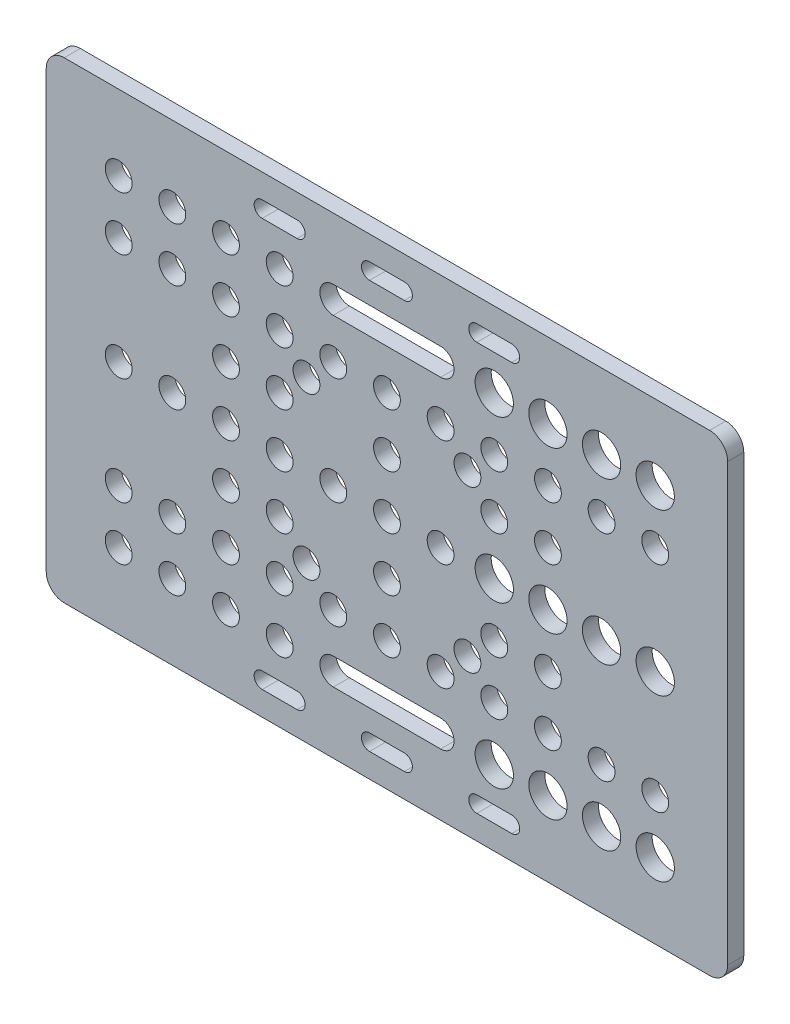
SolidWorks part; units mm, degrees
ref_plane "Plan de face" through (0, 0, 0) normal (0, 0, 1) x (1, 0, 0)
ref_plane "Plan de dessus" through (0, 0, 0) normal (0, 1, 0) x (1, 0, 0)
ref_plane "Plan de droite" through (0, 0, 0) normal (1, 0, 0) x (0, 0, -1)
sketch "Esquisse1" plane through (0, 0, 0) normal (0, 0, 1) x (1, 0, 0)
  line L0 (0, -44) -> (0, 44) construction
  line L1 (-60.14, -44) -> (60.14, -44)
  line L2 (-63.5, -40.64) -> (-63.5, 40.64)
  line L3 (-60.14, 44) -> (60.14, 44)
  line L4 (63.5, -40.64) -> (63.5, 40.64)
  line L5 (-63.5, -44) -> (63.5, 44) construction
  line L6 (-63.5, 44) -> (63.5, -44) construction
  line L7 (-10, -30) -> (10, -30) construction
  line L8 (-63.5, 0) -> (63.5, 0) construction
  line L9 (-10, -27.5) -> (10, -27.5)
  line L10 (-10, -32.5) -> (10, -32.5)
  line L11 (-23.25, -38.02) -> (-16.75, -38.02) construction
  line L12 (-23.25, -36.52) -> (-16.75, -36.52)
  line L13 (-23.25, -39.52) -> (-16.75, -39.52)
  line L14 (-20, -38.02) -> (-20, -30) construction
  line L15 (-3.25, -38.02) -> (3.25, -38.02) construction
  line L16 (-3.25, -36.52) -> (3.25, -36.52)
  line L17 (-3.25, -39.52) -> (3.25, -39.52)
  line L18 (16.75, -38.02) -> (23.25, -38.02) construction
  line L19 (16.75, -36.52) -> (23.25, -36.52)
  line L20 (16.75, -39.52) -> (23.25, -39.52)
  line L21 (-30, 0) -> (-30, -20) construction
  line L22 (-20, -10) -> (-10, -20) construction
  line L23 (-10, 30) -> (10, 30) construction
  line L24 (10, -20) -> (20, -10) construction
  line L25 (-10, 27.5) -> (10, 27.5)
  line L26 (-10, 32.5) -> (10, 32.5)
  line L27 (-23.25, 38.02) -> (-16.75, 38.02) construction
  line L28 (-23.25, 36.52) -> (-16.75, 36.52)
  line L29 (-23.25, 39.52) -> (-16.75, 39.52)
  line L30 (-3.25, 38.02) -> (3.25, 38.02) construction
  line L31 (-3.25, 36.52) -> (3.25, 36.52)
  line L32 (-3.25, 39.52) -> (3.25, 39.52)
  line L33 (16.75, 38.02) -> (23.25, 38.02) construction
  line L34 (16.75, 36.52) -> (23.25, 36.52)
  line L35 (16.75, 39.52) -> (23.25, 39.52)
  line L36 (10, 20) -> (20, 10) construction
  line L37 (-20, 10) -> (-10, 20) construction
  line L38 (-20, 38.02) -> (-20, 30) construction
  line L39 (-10, 30) -> (10, -30) construction
  line L40 (-10, -30) -> (10, 30) construction
  arc A0 (-60.14, -44) -> (-63.5, -40.64) centre (-60.14, -40.64) cw
  arc A1 (60.14, -44) -> (63.5, -40.64) centre (60.14, -40.64) ccw
  arc A2 (60.14, 44) -> (63.5, 40.64) centre (60.14, 40.64) cw
  arc A3 (-63.5, 40.64) -> (-60.14, 44) centre (-60.14, 40.64) cw
  circle A4 centre (0, -20) radius 2.5
  circle A5 centre (10, -20) radius 2.5
  circle A6 centre (20, -20) radius 2.5
  circle A7 centre (30, -20) radius 2.5
  circle A8 centre (40, -20) radius 2.5
  circle A9 centre (50, -20) radius 2.5
  circle A10 centre (-10, -20) radius 2.5
  circle A11 centre (-20, -20) radius 2.5
  circle A12 centre (-30, -20) radius 2.5
  circle A13 centre (-40, -20) radius 2.5
  circle A14 centre (-50, -20) radius 2.5
  circle A15 centre (-50, -30) radius 2.5
  circle A16 centre (-40, -30) radius 2.5
  circle A17 centre (-30, -30) radius 2.5
  circle A18 centre (-20, -30) radius 2.5
  circle A19 centre (50, -30) radius 3.57
  circle A20 centre (40, -30) radius 3.57
  circle A21 centre (30, -30) radius 3.57
  circle A22 centre (20, -30) radius 3.57
  arc A23 (-10, -27.5) -> (-10, -32.5) centre (-10, -30) ccw
  arc A24 (10, -32.5) -> (10, -27.5) centre (10, -30) ccw
  arc A25 (-23.25, -36.52) -> (-23.25, -39.52) centre (-23.25, -38.02) ccw
  arc A26 (-16.75, -39.52) -> (-16.75, -36.52) centre (-16.75, -38.02) ccw
  arc A27 (-3.25, -36.52) -> (-3.25, -39.52) centre (-3.25, -38.02) ccw
  arc A28 (3.25, -39.52) -> (3.25, -36.52) centre (3.25, -38.02) ccw
  arc A29 (16.75, -36.52) -> (16.75, -39.52) centre (16.75, -38.02) ccw
  arc A30 (23.25, -39.52) -> (23.25, -36.52) centre (23.25, -38.02) ccw
  circle A31 centre (-50, 0) radius 2.5
  circle A32 centre (-40, 0) radius 2.5
  circle A33 centre (-30, 0) radius 2.5
  circle A34 centre (-20, 0) radius 2.5
  circle A35 centre (-10, 0) radius 2.5
  circle A36 centre (0, 0) radius 2.5
  circle A37 centre (10, 0) radius 2.5
  circle A38 centre (20, 0) radius 3.57
  circle A39 centre (30, 0) radius 3.57
  circle A40 centre (40, 0) radius 3.57
  circle A41 centre (50, 0) radius 3.57
  circle A42 centre (-30, -10) radius 2.5
  circle A43 centre (-20, -10) radius 2.5
  circle A44 centre (20, -10) radius 2.5
  circle A45 centre (30, -10) radius 2.5
  circle A46 centre (0, -10) radius 2.5
  circle A47 centre (-15, -15) radius 2.5
  circle A48 centre (15, -15) radius 2.5
  circle A49 centre (50, 0) radius 2.5 [skipped]
  circle A50 centre (40, 0) radius 2.5 [skipped]
  circle A51 centre (30, 0) radius 2.5 [skipped]
  circle A52 centre (20, 0) radius 2.5 [skipped]
  arc A53 (-10, 27.5) -> (-10, 32.5) centre (-10, 30) cw
  arc A54 (10, 32.5) -> (10, 27.5) centre (10, 30) cw
  arc A55 (-23.25, 36.52) -> (-23.25, 39.52) centre (-23.25, 38.02) cw
  arc A56 (-16.75, 39.52) -> (-16.75, 36.52) centre (-16.75, 38.02) cw
  arc A57 (-3.25, 36.52) -> (-3.25, 39.52) centre (-3.25, 38.02) cw
  arc A58 (3.25, 39.52) -> (3.25, 36.52) centre (3.25, 38.02) cw
  arc A59 (16.75, 36.52) -> (16.75, 39.52) centre (16.75, 38.02) cw
  arc A60 (23.25, 39.52) -> (23.25, 36.52) centre (23.25, 38.02) cw
  circle A61 centre (15, 15) radius 2.5
  circle A62 centre (-15, 15) radius 2.5
  circle A63 centre (0, 10) radius 2.5
  circle A64 centre (30, 10) radius 2.5
  circle A65 centre (20, 10) radius 2.5
  circle A66 centre (-20, 10) radius 2.5
  circle A67 centre (-30, 10) radius 2.5
  circle A68 centre (20, 30) radius 3.57
  circle A69 centre (30, 30) radius 3.57
  circle A70 centre (40, 30) radius 3.57
  circle A71 centre (50, 30) radius 3.57
  circle A72 centre (-20, 30) radius 2.5
  circle A73 centre (-30, 30) radius 2.5
  circle A74 centre (-40, 30) radius 2.5
  circle A75 centre (-50, 30) radius 2.5
  circle A76 centre (-50, 20) radius 2.5
  circle A77 centre (-40, 20) radius 2.5
  circle A78 centre (-30, 20) radius 2.5
  circle A79 centre (-20, 20) radius 2.5
  circle A80 centre (-10, 20) radius 2.5
  circle A81 centre (50, 20) radius 2.5
  circle A82 centre (40, 20) radius 2.5
  circle A83 centre (30, 20) radius 2.5
  circle A84 centre (20, 20) radius 2.5
  circle A85 centre (10, 20) radius 2.5
  circle A86 centre (0, 20) radius 2.5
  point P0 (0, 0)
  point P62 (0, -30)
  point P69 (-20, -38.02)
  point P78 (0, -38.02)
  point P85 (20, -38.02)
  point P135 (0, 30)
  point P142 (-20, 38.02)
  point P149 (0, 38.02)
  point P156 (20, 38.02)
  dimension "D3" = 3.36
  dimension "D4" = 5
  dimension "D10" = 7.14
  dimension "D12" = 5
  dimension "D20" = 5
  dimension "D24" = 5
  dimension "D25" = 4
  dimension "D26" = 5
  dimension "D27" = 7.14
  dimension "D28" = 5
  dimension "D1" = 88
  dimension "D2" = 127
  dimension "D5" = 10
  dimension "D13" = 10
  dimension "D14" = 10
  dimension "D15" = 10
  dimension "D16" = 3
  dimension "D17" = 6.5
  dimension "D18" = 5.98
  dimension "D23" = 10
  dimension "D29" = 5
  dimension "D6" = 6
  dimension "D7" = 6
  dimension "D8" = 2
  dimension "D9" = 4
  dimension "D11" = 4
  dimension "D19" = 3
  dimension "D21" = 11
  dimension "D22" = 2
extrude "Boss.-Extru.1" add sketch "Esquisse1" along normal mid plane 3
